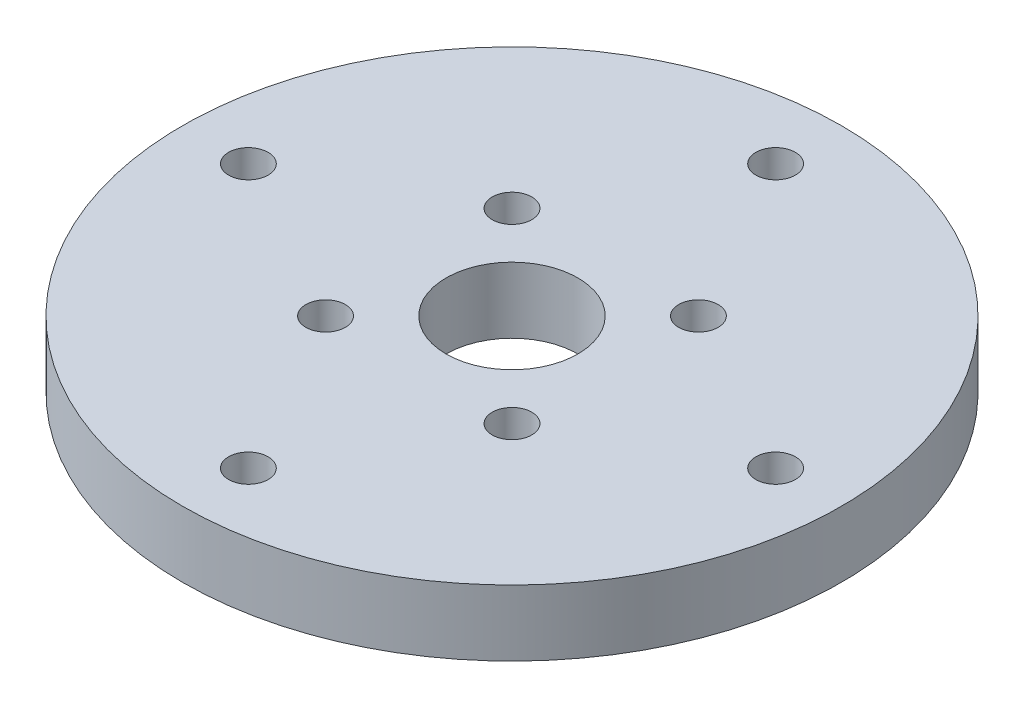
SolidWorks part; units mm, degrees
ref_plane "前视基准面" through (0, 0, 0) normal (0, 0, 1) x (1, 0, 0)
ref_plane "上视基准面" through (0, 0, 0) normal (0, 1, 0) x (1, 0, 0)
ref_plane "右视基准面" through (0, 0, 0) normal (1, 0, 0) x (0, 0, -1)
sketch "草图1" plane through (0, 0, 0) normal (0, 1, 0) x (1, 0, 0)
  line L1 (10, -10) -> (-10, -10) construction
  line L2 (10, -10) -> (10, 10) construction
  line L3 (10, 10) -> (-10, 10) construction
  line L4 (-10, -10) -> (-10, 10) construction
  line L5 (10, -10) -> (-10, 10) construction
  line L6 (10, 10) -> (-10, -10) construction
  circle A0 centre (0, 0) radius 25
  circle A1 centre (0, 0) radius 20 construction
  circle A6 centre (0, 20) radius 1.5
  circle A7 centre (20, 0) radius 1.5
  circle A8 centre (0, -20) radius 1.5
  circle A9 centre (-20, 0) radius 1.5
  circle A10 centre (0, 0) radius 10 construction
  circle A11 centre (-7.0711, 7.0711) radius 1.5
  circle A12 centre (7.0711, 7.0711) radius 1.5
  circle A13 centre (7.0711, -7.0711) radius 1.5
  circle A14 centre (-7.0711, -7.0711) radius 1.5
  circle A15 centre (0, 0) radius 5
  point P23 (0, 0)
  point P29 (0, 0)
  dimension "D1" = 50
  dimension "D2" = 40
  dimension "D5" = 20
  dimension "D6" = 3
  dimension "D7" = 4
  dimension "D8" = 10
  dimension "D9" = 3
  dimension "D3" = 20
  dimension "D4" = 20
  dimension "D10" = 4
extrude "凸台-拉伸1" add sketch "草图1" along normal blind 5
